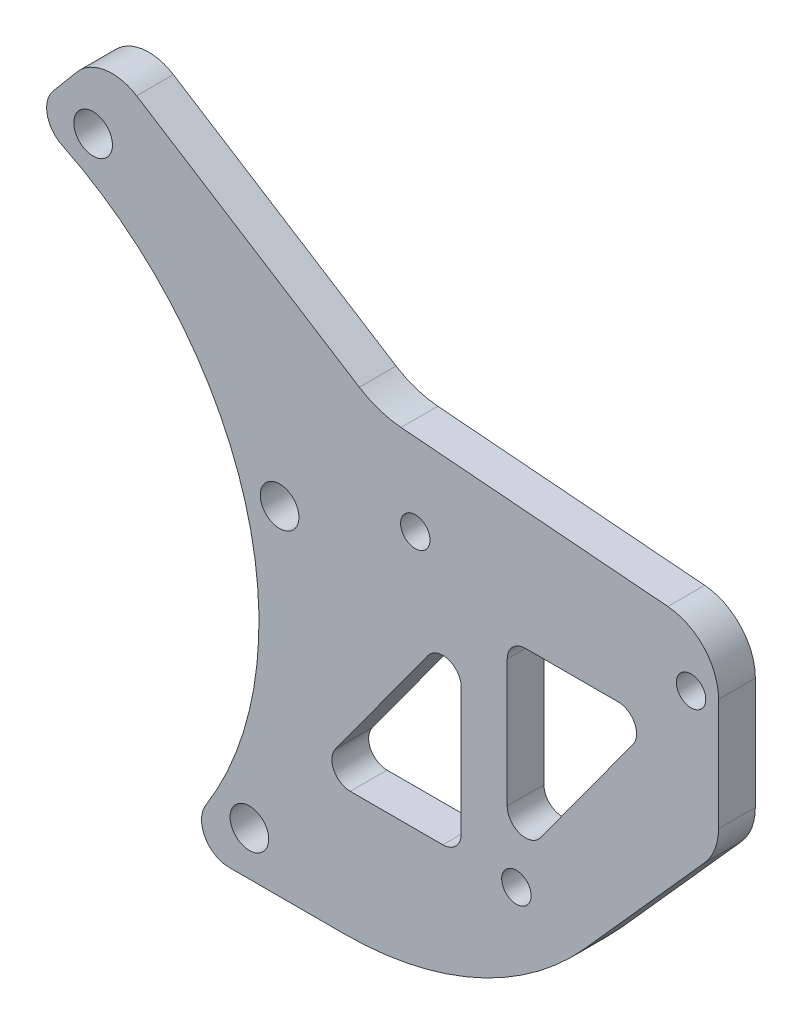
SolidWorks part; units mm, degrees
material "Thornel Mat VMA"
ref_plane "前视基准面" through (0, 0, 0) normal (0, 0, 1) x (1, 0, 0)
ref_plane "上视基准面" through (0, 0, 0) normal (0, 1, 0) x (1, 0, 0)
ref_plane "右视基准面" through (0, 0, 0) normal (1, 0, 0) x (0, 0, -1)
other "Configuration Table"
sketch "草图3" plane through (0, 0, 0) normal (0, 0, 1) x (1, 0, 0)
  line L0 (0, 0) -> (19.9569, 36.9557) construction
  line L1 (0, 0) -> (40.2433, 12.02) construction
  line L2 (0, 0) -> (36.9557, -19.9569) construction
  line L3 (0, 0) -> (0, 51.3306) construction
  line L4 (0, 0) -> (12.9968, 35.7083) construction
  line L5 (12.9968, 35.7083) -> (20.9968, 45.2423)
  line L6 (20.9968, 45.2423) -> (50.9968, 26.2423)
  line L7 (50.9968, 26.2423) -> (87.9968, 23.2423)
  line L8 (87.9968, 23.2423) -> (87.9968, 3.2423)
  line L9 (87.9968, 3.2423) -> (62.9968, -24.7577)
  line L10 (62.9968, -24.7577) -> (28.8281, -24.7577)
  circle A0 centre (0, 0) radius 42 construction
  circle A1 centre (19.9569, 36.9557) radius 2.1
  circle A2 centre (40.2433, 12.02) radius 2.1
  circle A3 centre (36.9557, -19.9569) radius 2.1
  circle A4 centre (0, 0) radius 38
  dimension "D1" = 84
  dimension "D2" = 4.2
  dimension "D6" = 76
  dimension "D3" = 45
  dimension "D4" = 45
  dimension "D5" = 28.37
  dimension "D7" = 20
  dimension "D8" = 8
  dimension "D9" = 30
  dimension "D10" = 37
  dimension "D11" = 160
  dimension "D12" = 19
  dimension "D13" = 3
  dimension "D14" = 20
  dimension "D15" = 28
  dimension "D16" = 25
extrude "凸台-拉伸2" add sketch "草图3" along normal blind 4
fillet "圆角1" radius 5 1 edges at (20.9968, 45.2423, 2)
fillet "圆角3" radius 6 2 edges at (87.9968, 3.2423, 2) (87.9968, 23.2423, 2)
fillet "圆角4" radius 10 1 edges at (50.9968, 26.2423, 2)
fillet "圆角5" radius 35 1 edges at (62.9968, -24.7577, 2)
sketch "草图4" plane through (0, 0, 4) normal (0, 0, 1) x (1, 0, 0)
  circle A0 centre (55.0033, 17) radius 1.6
  circle A1 centre (40.2433, 12.02) radius 2.1 construction
  circle A2 centre (40.2433, 12.02) radius 2.1
  circle A3 centre (85.0033, 17) radius 1.6
  dimension "D3" = 3.2
  dimension "D1" = 14.76
  dimension "D2" = 4.98
  dimension "D4" = 30
extrude "切除-拉伸1" cut sketch "草图4" against normal up to next (4 mm away)
sketch "草图5" plane through (0, 0, 4) normal (0, 0, 1) x (1, 0, 0)
  line L0 (65.0033, 12) -> (81.0033, 12)
  line L1 (81.0033, 12) -> (65.0033, -10)
  line L2 (65.0033, -10) -> (65.0033, 12)
  line L3 (60.0033, 11) -> (60.0033, -11)
  line L4 (60.0033, -11) -> (44.0033, -11)
  line L5 (44.0033, -11) -> (60.0033, 11)
  circle A0 centre (55.0033, 17) radius 1.6 construction
  circle A1 centre (55.0033, 17) radius 1.6
  dimension "D1" = 5
  dimension "D2" = 22
  dimension "D3" = 16
  dimension "D4" = 10
  dimension "D5" = 5
  dimension "D6" = 16
  dimension "D7" = 22
  dimension "D8" = 1
extrude "切除-拉伸2" cut sketch "草图5" against normal up to next (4 mm away)
fillet "圆角7" radius 2 2 edges at (60.0033, -11, 2) (65.0033, 12, 2)
fillet "圆角8" radius 2 4 edges at (81.0033, 12, 2) (44.0033, -11, 2) (65.0033, -10, 2) (60.0033, 11, 2)
fillet "圆角9" radius 3 2 edges at (28.8281, -24.7577, 2) (12.9968, 35.7083, 2)
sketch "草图7" plane through (0, 0, 4) normal (0, 0, 1) x (1, 0, 0)
  line L0 (55.0033, 17) -> (85.0033, 17) construction
  line L1 (70.0033, 17) -> (70.0033, -33.6938) construction
  circle A0 centre (66.0033, -11) radius 1.6
  dimension "D1" = 3.2
  dimension "D2" = 4
  dimension "D3" = 28
extrude "切除-拉伸3" cut sketch "草图7" against normal blind 10
